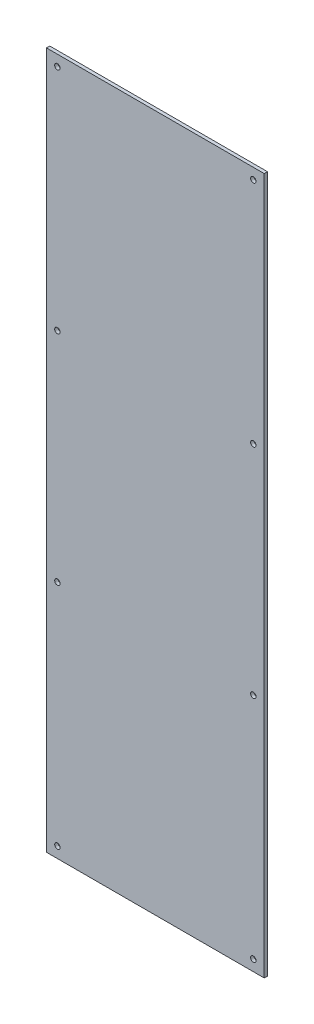
SolidWorks part; units mm, degrees
material "Acrylic (Medium-high impact)"
ref_plane "Front Plane" through (0, 0, 0) normal (0, 0, 1) x (1, 0, 0)
ref_plane "Top Plane" through (0, 0, 0) normal (0, 1, 0) x (1, 0, 0)
ref_plane "Right Plane" through (0, 0, 0) normal (1, 0, 0) x (0, 0, -1)
sketch "Sketch2" plane through (0, 0, 0) normal (0, 0, 1) x (1, 0, 0)
  line L1 (-27.1074, 80.9917) -> (172.8926, 80.9917)
  line L2 (-27.1074, 80.9917) -> (-27.1074, -559.0083)
  line L3 (-27.1074, -559.0083) -> (172.8926, -559.0083)
  line L4 (172.8926, 80.9917) -> (172.8926, -559.0083)
  dimension "D1" = 200
  dimension "D2" = 640
extrude "Boss-Extrude1" add sketch "Sketch2" along normal blind 3
sketch "Sketch3" plane through (0, 0, 3) normal (0, 0, 1) x (1, 0, 0)
  line L0 (-27.1074, -559.0083) -> (172.8926, -559.0083) construction
  line L1 (172.8926, -559.0083) -> (172.8926, 80.9917) construction
  line L2 (172.8926, 80.9917) -> (-27.1074, 80.9917) construction
  circle A0 centre (162.8926, -549.0083) radius 2.5
  circle A1 centre (-17.1074, -549.0083) radius 2.5
  circle A2 centre (-17.1074, -339.0083) radius 2.5
  circle A3 centre (-17.1074, 70.9917) radius 2.5
  circle A4 centre (-17.1074, -139.0083) radius 2.5
  circle A6 centre (162.8926, 70.9917) radius 2.5
  circle A7 centre (162.8926, -139.0083) radius 2.5
  circle A9 centre (162.8926, -339.0083) radius 2.5
  dimension "D1" = 5
  dimension "D3" = 10
  dimension "D5" = 10
  dimension "D6" = 10
  dimension "D9" = 10
  dimension "D14" = 10
  dimension "D4" = 210
  dimension "D8" = 10
  dimension "D10" = 200
  dimension "D2" = 10
  dimension "D7" = 210
  dimension "D11" = 210
extrude "Cut-Extrude1" cut sketch "Sketch3" against normal through all
